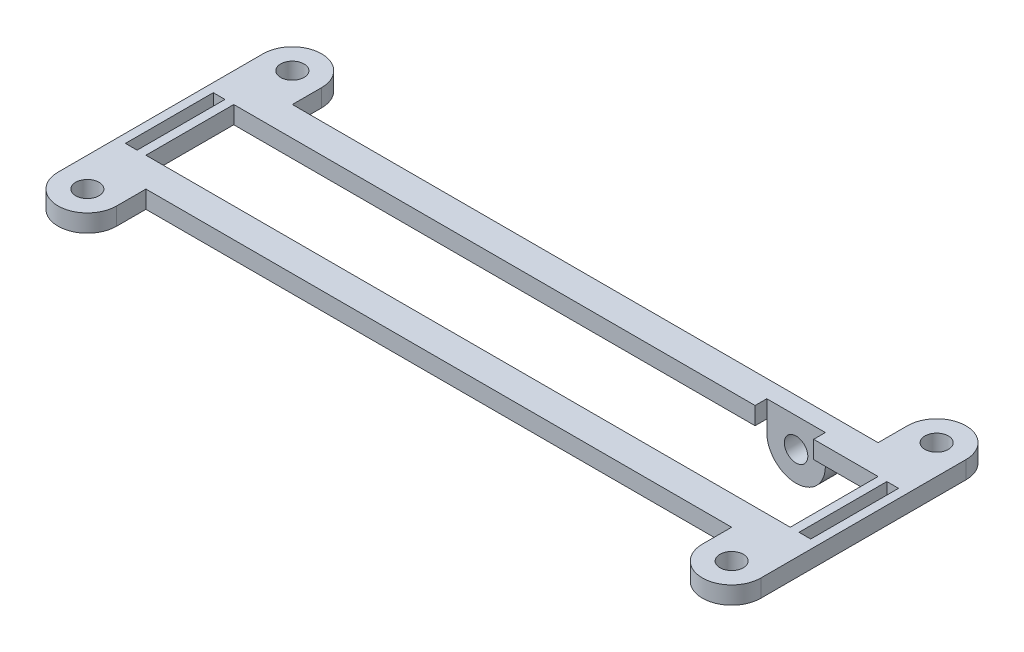
SolidWorks part; units mm, degrees
ref_plane "Front Plane" through (0, 0, 0) normal (0, 0, 1) x (1, 0, 0)
ref_plane "Top Plane" through (0, 0, 0) normal (0, 1, 0) x (1, 0, 0)
ref_plane "Right Plane" through (0, 0, 0) normal (1, 0, 0) x (0, 0, -1)
sketch "Sketch1" plane through (0, 0, 0) normal (0, 1, 0) x (1, 0, 0)
  line L0 (0, 25) -> (0, 30)
  line L1 (0, 0) -> (120, 0)
  line L2 (0, 0) -> (0, 25)
  line L3 (0, 25) -> (120, 25)
  line L4 (120, 0) -> (120, 25)
  line L5 (5, 20) -> (115, 20)
  line L6 (5, 20) -> (5, 5)
  line L7 (5, 5) -> (115, 5)
  line L8 (115, 20) -> (115, 5)
  line L9 (10, 25) -> (10, 30)
  line L10 (60, 20) -> (60, 5) construction
  line L11 (60, 12.5) -> (115, 12.5) construction
  line L12 (120, 25) -> (120, 30)
  line L13 (110, 25) -> (110, 30)
  line L14 (120, 0) -> (120, -5)
  line L15 (110, 0) -> (110, -5)
  line L16 (0, 0) -> (0, -5)
  line L17 (10, 0) -> (10, -5)
  circle A0 centre (5, 30) radius 5
  circle A1 centre (5, 30) radius 2
  circle A2 centre (115, 30) radius 5
  circle A3 centre (115, 30) radius 2
  circle A4 centre (115, -5) radius 5
  circle A5 centre (115, -5) radius 2
  circle A6 centre (5, -5) radius 5
  circle A7 centre (5, -5) radius 2
  point P22 (120, 27.5)
  dimension "D10" = 4
  dimension "D12" = 4
  dimension "D16" = 4
  dimension "D19" = 4
  dimension "D1" = 120
  dimension "D2" = 25
  dimension "D3" = 5
  dimension "D4" = 5
  dimension "D5" = 5
  dimension "D6" = 5
  dimension "D7" = 5
  dimension "D8" = 5
  dimension "D9" = 10
  dimension "D11" = 10
  dimension "D13" = 5
  dimension "D14" = 5
  dimension "D15" = 10
  dimension "D17" = 5
  dimension "D18" = 5
extrude "Boss-Extrude1" add sketch "Sketch1" along normal blind 3 contours A0 A1 | A0 L0 L3 | A0 L3 L9 | L1 L4 L3 L2 L5 L8 L7 L6 | A6 L1 L16 | A6 L17 L1 | A6 A7 | A2 L13 L3 | A2 A3 | A2 L3 L12 | A4 L1 L15 | A4 L14 L1 | A4 A5
sketch "Sketch2" plane through (0, 3, 0) normal (0, 1, 0) x (1, 0, 0)
  line L0 (5, 20) -> (115, 20) construction
  line L1 (116.5, 20) -> (118.5, 20)
  line L2 (116.5, 20) -> (116.5, 5)
  line L3 (116.5, 5) -> (118.5, 5)
  line L4 (118.5, 20) -> (118.5, 5)
  line L5 (5, 5) -> (115, 5) construction
  line L6 (115, 20) -> (115, 5) construction
  line L7 (60, 20) -> (60, 5) construction
  line L8 (3.5, 5) -> (1.5, 5)
  line L9 (1.5, 20) -> (1.5, 5)
  line L10 (3.5, 20) -> (1.5, 20)
  line L11 (3.5, 20) -> (3.5, 5)
  dimension "D1" = 1.5
  dimension "D2" = 2
extrude "Cut-Extrude1" cut sketch "Sketch2" against normal up to surface (3 mm away) up to face at (60, 0, -12.5)
sketch "Sketch3" plane through (0, 0, -25) normal (0, 0, -1) x (-1, 0, 0)
  line L0 (-10, 0) -> (-110, 0) construction
  line L1 (-110, 3) -> (-110, 0) construction
  line L2 (-104, -2.01) -> (-104, 0)
  line L3 (-94, -2.01) -> (-94, 0)
  line L4 (-104, 0) -> (-94, 0)
  circle A0 centre (-99, -2.01) radius 2
  circle A1 centre (-99, -2.01) radius 5
  line M3 (-110, 0) -> (-10, 0)
  dimension "D1" = 4
  dimension "D3" = 10
  dimension "D2" = 2.01
  dimension "D4" = 11
extrude "Boss-Extrude3" add sketch "Sketch3" against normal blind 3 contours A1 L4 A0 | A1 L3 M3 | A1 L2 M3
sketch "Sketch4" plane through (0, 0, -20) normal (0, 0, 1) x (1, 0, 0)
  line L0 (5, 0) -> (115, 0) construction
  line L1 (104, 0) -> (94, 0)
  line L2 (104, 0) -> (104, 3)
  line L3 (104, 3) -> (94, 3)
  line L4 (94, 0) -> (94, 3)
  line L5 (5, 3) -> (115, 3) construction
  line L6 (115, 3) -> (115, 0) construction
  dimension "D1" = 10
  dimension "D2" = 11
extrude "Cut-Extrude2" cut sketch "Sketch4" against normal blind 2
